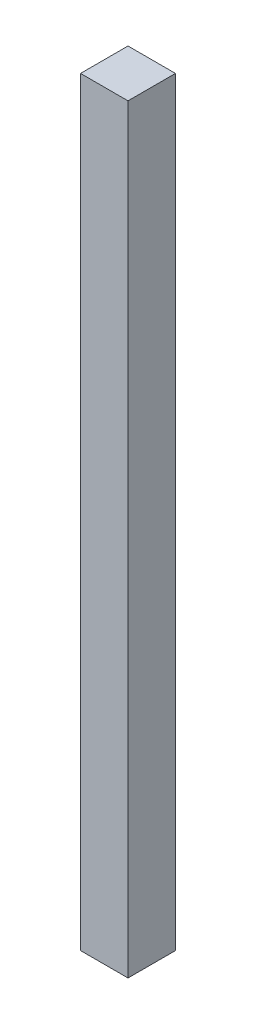
SolidWorks part; units mm, degrees
ref_plane "Front Plane" through (0, 0, 0) normal (0, 0, 1) x (1, 0, 0)
ref_plane "Top Plane" through (0, 0, 0) normal (0, 1, 0) x (1, 0, 0)
ref_plane "Right Plane" through (0, 0, 0) normal (1, 0, 0) x (0, 0, -1)
sketch "Sketch1" plane through (0, 0, 0) normal (0, 1, 0) x (1, 0, 0)
  line L1 (0, 0) -> (-25, 0)
  line L2 (0, 0) -> (0, -25)
  line L3 (0, -25) -> (-25, -25)
  line L4 (-25, 0) -> (-25, -25)
  dimension "D1" = 25
  dimension "D2" = 25
extrude "Boss-Extrude1" add sketch "Sketch1" along normal blind 400 contours L1 L4 L3 L2
